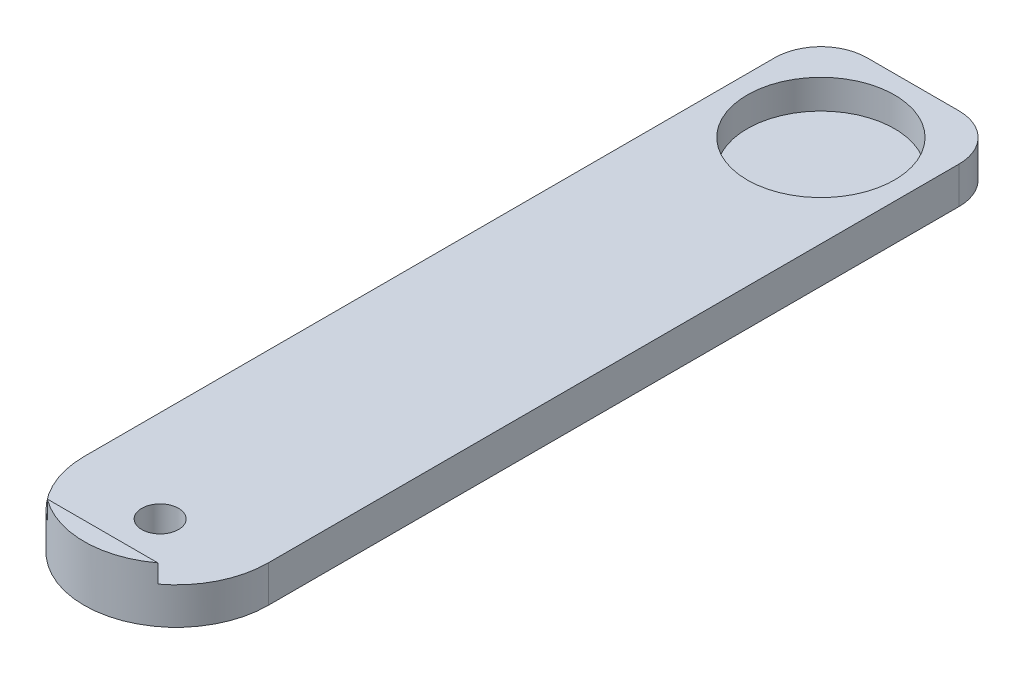
SolidWorks part; units mm, degrees
ref_plane "Front Plane" through (0, 0, 0) normal (0, 0, 1) x (1, 0, 0)
ref_plane "Top Plane" through (0, 0, 0) normal (0, 1, 0) x (1, 0, 0)
ref_plane "Right Plane" through (0, 0, 0) normal (1, 0, 0) x (0, 0, -1)
sketch "Sketch1" plane through (0, 0, 0) normal (0, 1, 0) x (1, 0, 0)
  line L1 (-10, -40) -> (10, -40)
  line L2 (-10, -40) -> (-10, 40)
  line L3 (-10, 40) -> (10, 40)
  line L4 (10, -40) -> (10, 40)
  line L5 (-10, -40) -> (10, 40) construction
  line L6 (-10, 40) -> (10, -40) construction
  point P0 (0, 0)
  dimension "D1" = 20
  dimension "D2" = 80
extrude "Boss-Extrude1" add sketch "Sketch1" along normal blind 4
sketch "Sketch8" plane through (0, 4, 0) normal (0, 1, 0) x (1, 0, 0)
  line L0 (-10, -40) -> (10, -40) construction
  circle A0 centre (0, -40) radius 10
extrude "Boss-Extrude2" add sketch "Sketch8" against normal blind 4
sketch "Sketch9" plane through (0, 4, 0) normal (0, 1, 0) x (1, 0, 0)
  line L0 (0, -31.0741) -> (0, 30) construction
  line L1 (0, 30) -> (0, 40) construction
  line L2 (10, 40) -> (-10, 40) construction
  circle A0 centre (0, 30) radius 8
  dimension "D1" = 10
  dimension "D2" = 16
extrude "Cut-Extrude1" cut sketch "Sketch9" against normal blind 3.175 contours A0
sketch "Sketch10" plane through (0, 4, 0) normal (0, 1, 0) x (1, 0, 0)
  line L0 (0, -50) -> (0, -41.7425)
  arc A0 (-10, -40) -> (10, -40) centre (0, -40) ccw construction
  circle A1 centre (0, -41.7425) radius 2
extrude "Cut-Extrude2" cut sketch "Sketch10" against normal through all contours A1
sketch "Sketch11" plane through (0, 4, 0) normal (0, 1, 0) x (1, 0, 0)
  line L0 (-6, -48) -> (6, -48)
  arc A0 (-10, -40) -> (10, -40) centre (0, -40) ccw construction
  arc A1 (-6, -48) -> (6, -48) centre (0, -40) ccw
  point P5 (0, -50)
  dimension "D1" = 2
extrude "Boss-Extrude3" add sketch "Sketch11" along normal blind 2
fillet "Fillet1" radius 5 2 edges at (10, 2, -40) (-10, 2, -40)
